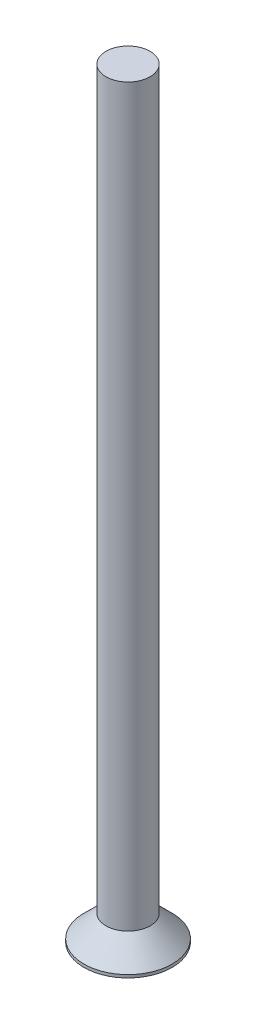
SolidWorks part; units mm, degrees
ref_plane "Front Plane" through (0, 0, 0) normal (0, 0, 1) x (1, 0, 0)
ref_plane "Top Plane" through (0, 0, 0) normal (0, 1, 0) x (1, 0, 0)
ref_plane "Right Plane" through (0, 0, 0) normal (1, 0, 0) x (0, 0, -1)
sketch "Sketch2" plane through (0, 0, 0) normal (0, 0, 1) x (1, 0, 0)
  line L1 (3, 0) -> (1.5, 1.5)
  line L2 (1.5, 1.5) -> (1.5, 51.5)
  line L3 (1.5, 51.5) -> (-1.5, 51.5)
  line L4 (-1.5, 51.5) -> (-1.5, 1.5)
  line L5 (-1.5, 1.5) -> (-3, 0)
  line L6 (0, 1.5) -> (0, 51.5)
  line L7 (1.5, 1.5) -> (-1.5, 1.5) construction
  line L8 (-3, 0) -> (-3, -0.2)
  line L9 (-3, -0.2) -> (3, -0.2)
  line L10 (3, -0.2) -> (3, 0)
  line L11 (0, 1.5) -> (0, -0.2)
  dimension "D1" = 45
  dimension "D2" = 45
  dimension "D3" = 6
  dimension "D4" = 3
  dimension "D5" = 1.7
  dimension "D6" = 50
revolve "Revolve1" add sketch "Sketch2" angle 360 about L6
